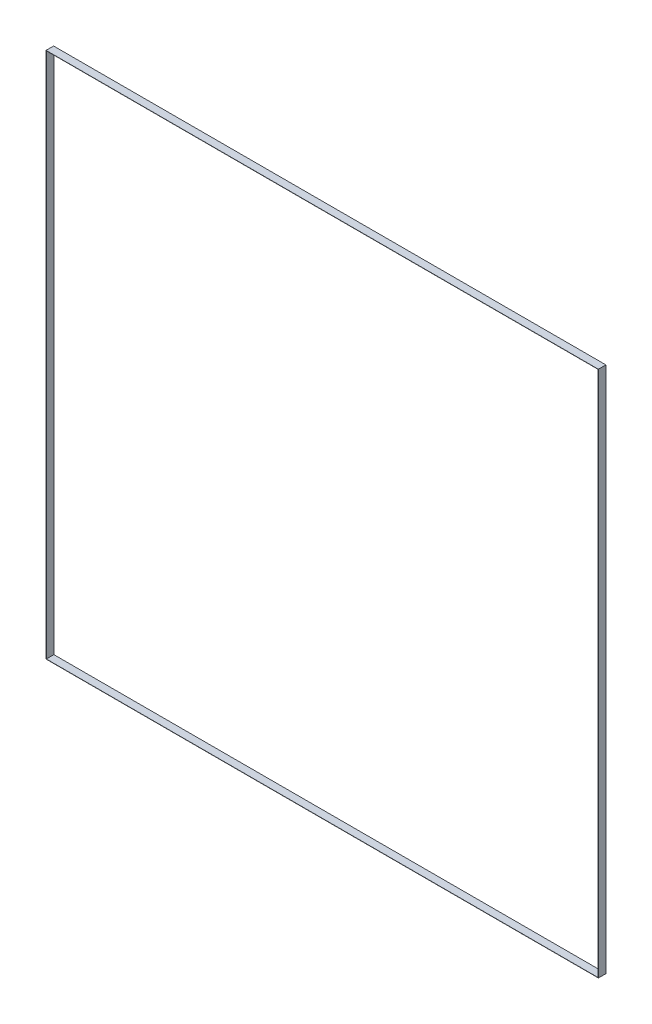
SolidWorks part; units mm, degrees
material "PBT General Purpose"
ref_plane "Front Plane" through (0, 0, 0) normal (0, 0, 1) x (1, 0, 0)
ref_plane "Top Plane" through (0, 0, 0) normal (0, 1, 0) x (1, 0, 0)
ref_plane "Right Plane" through (0, 0, 0) normal (1, 0, 0) x (0, 0, -1)
sketch "Sketch1" plane through (0, 0, 0) normal (0, 0, 1) x (1, 0, 0)
  line L1 (0, 0) -> (-22, 0)
  line L2 (0, 0) -> (0, 21)
  line L4 (-22, 0) -> (-22, 21)
  line L26 (-22, 21) -> (0, 21)
  line L31 (-0.01, 0.01) -> (-21.99, 0.01)
  line L32 (-0.01, 0.01) -> (-0.01, 20.99)
  line L33 (-0.01, 20.99) -> (-21.99, 20.99)
  line L34 (-21.99, 0.01) -> (-21.99, 20.99)
  dimension "D1" = 0.01
  dimension "D2" = 22
  dimension "D3" = 0.01
  dimension "D4" = 0.01
  dimension "D5" = 0.01
  dimension "D7" = 21
extrude "Boss-Extrude1" add sketch "Sketch1" along normal mid plane 0.3
equation "\"t\"= 0.3'thickness of the sheets"
equation "\"FlexJoint\"= 0.15'Width of flextures"
equation "\"FoldJoint\"= 0.4'Width of folding joints"
equation "\"AssembleAngle\"= 90'Angle of assembly parts"
equation "\"D1@Boss-Extrude1\"=\"t\""
